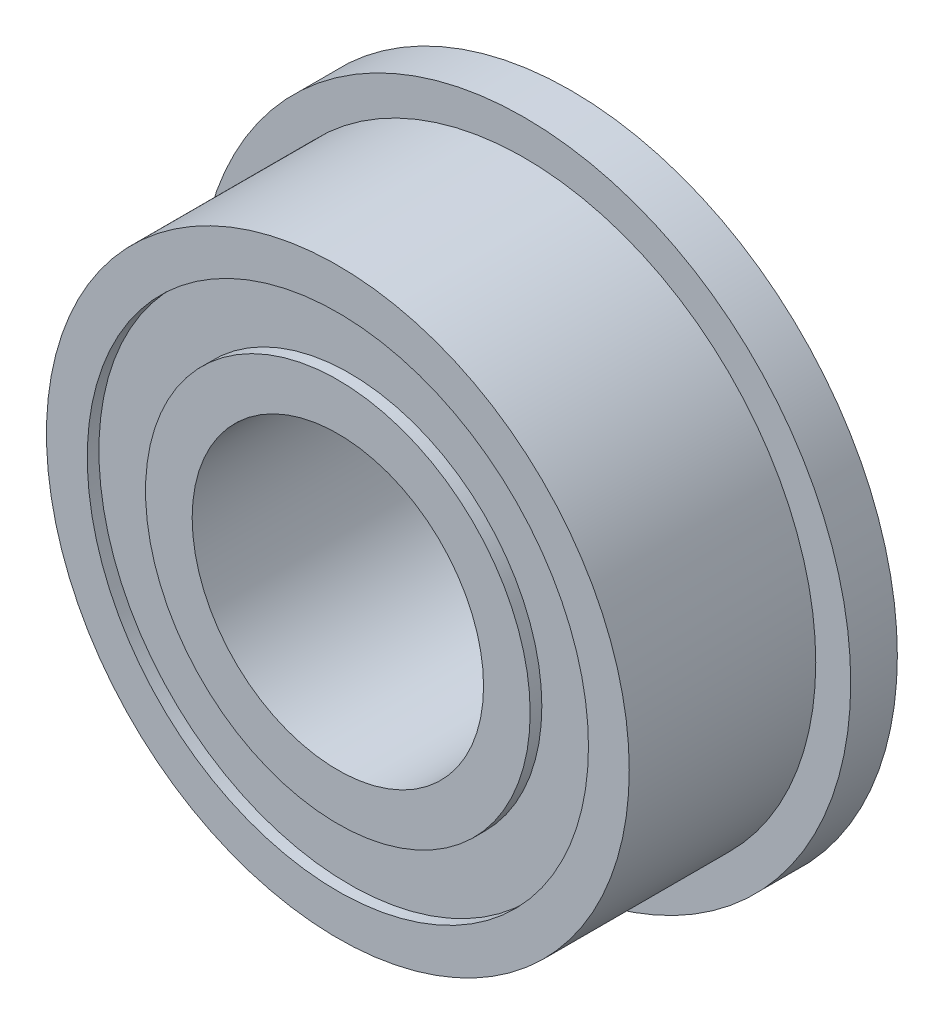
SolidWorks part; units mm, degrees
ref_plane "Front Plane" through (0, 0, 0) normal (0, 0, 1) x (1, 0, 0)
ref_plane "Top Plane" through (0, 0, 0) normal (0, 1, 0) x (1, 0, 0)
ref_plane "Right Plane" through (0, 0, 0) normal (1, 0, 0) x (0, 0, -1)
sketch "Sketch1" plane through (0, 0, 0) normal (0, 0, 1) x (1, 0, 0)
  circle A0 centre (0, 0) radius 5.6
  circle A1 centre (0, 0) radius 3.3
extrude "Flange" add sketch "Sketch1" along normal blind 0.8
ref_plane "Plane_z0_8" through (0, 0, 0.8) normal (0, 0, 1) x (1, 0, 0)
sketch "Sketch2" plane through (0, 0, 0.8) normal (0, 0, 1) x (1, 0, 0)
  circle A0 centre (0, 0) radius 5
  circle A1 centre (0, 0) radius 4.3
extrude "Outer_ring" add sketch "Sketch2" along normal blind 3.2
sketch "Sketch3" plane through (0, 0, 0) normal (0, 0, 1) x (1, 0, 0)
  circle A0 centre (0, 0) radius 3.3
  circle A1 centre (0, 0) radius 2.5
extrude "Inner_ring" add sketch "Sketch3" along normal blind 4
ref_plane "Plane_z1" through (0, 0, 1) normal (0, 0, 1) x (1, 0, 0)
sketch "Sketch4" plane through (0, 0, 1) normal (0, 0, 1) x (1, 0, 0)
  circle A0 centre (0, 0) radius 4.3
  circle A1 centre (0, 0) radius 3.3
extrude "Shields" add sketch "Sketch4" along normal blind 2.8
